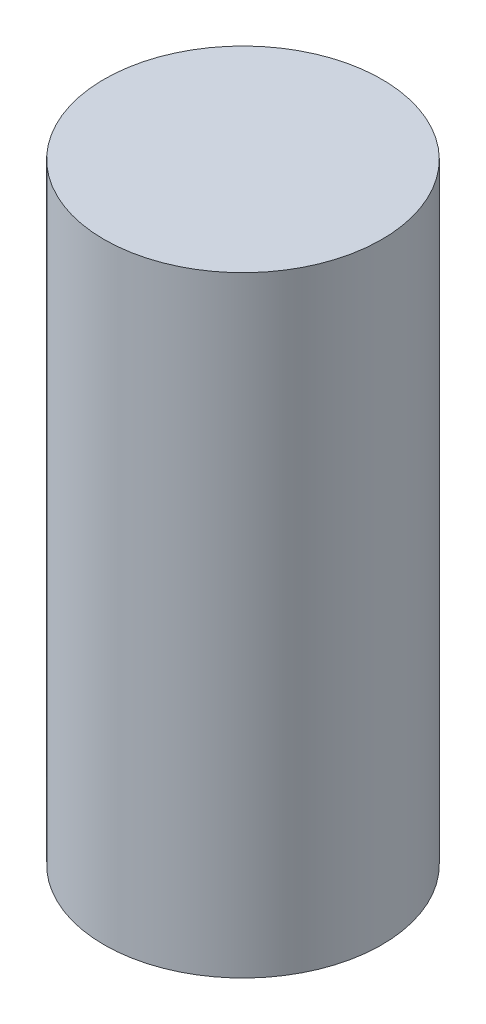
SolidWorks part; units mm, degrees
ref_plane "Спереди" through (0, 0, 0) normal (0, 0, 1) x (1, 0, 0)
ref_plane "Сверху" through (0, 0, 0) normal (0, 1, 0) x (1, 0, 0)
ref_plane "Справа" through (0, 0, 0) normal (1, 0, 0) x (0, 0, -1)
sketch "Эскиз1" plane through (0, 0, 0) normal (0, 1, 0) x (1, 0, 0)
  circle A0 centre (0, 0) radius 10
  dimension "D1" = 20
extrude "Бобышка-Вытянуть1" add sketch "Эскиз1" along normal blind 44
